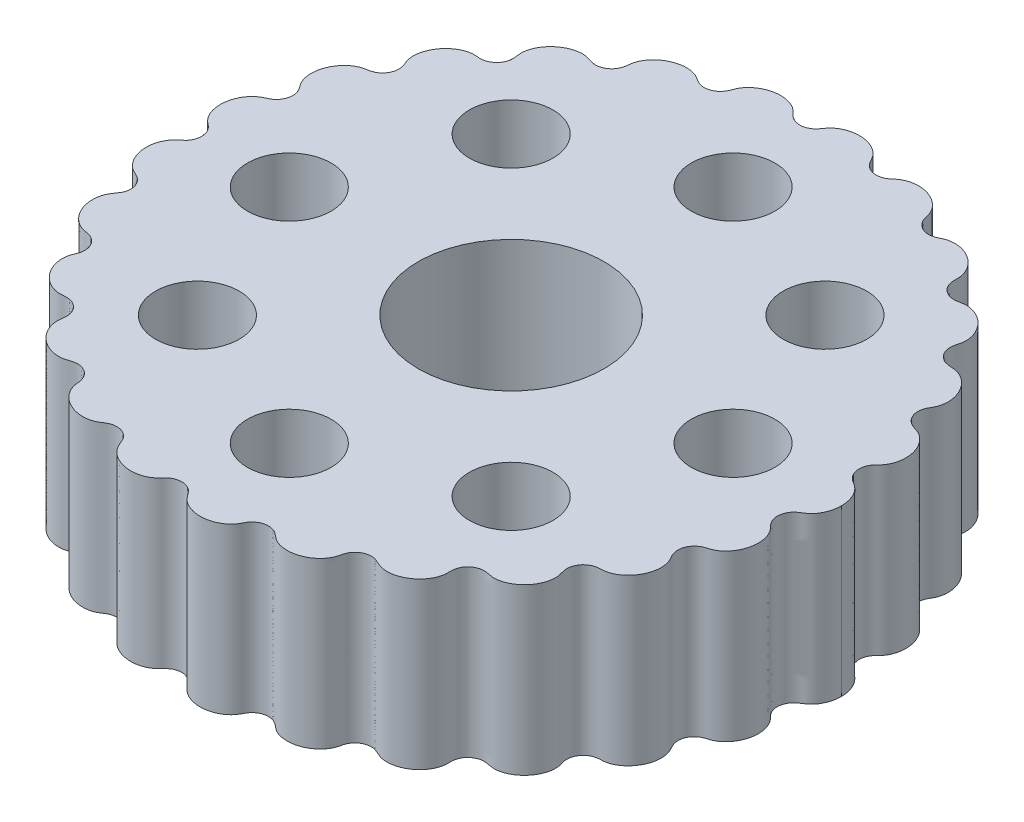
SolidWorks part; units mm, degrees
ref_plane "Front Plane" through (0, 0, 0) normal (0, 0, 1) x (1, 0, 0)
ref_plane "Top Plane" through (0, 0, 0) normal (0, 1, 0) x (1, 0, 0)
ref_plane "Right Plane" through (0, 0, 0) normal (1, 0, 0) x (0, 0, -1)
sketch "Sketch2" plane through (0, 0, 0) normal (0, 1, 0) x (1, 0, 0)
  line L0 (-31.5, 0) -> (33.5, 0) construction
  circle A0 centre (0, 0) radius 9
  circle A1 centre (0, 0) radius 21.5 construction
  circle A2 centre (0, 21.5) radius 4.05
  circle A3 centre (15.2028, 15.2028) radius 4.05
  circle A4 centre (21.5, 0) radius 4.05
  circle A5 centre (15.2028, -15.2028) radius 4.05
  circle A6 centre (0, -21.5) radius 4.05
  circle A7 centre (-15.2028, -15.2028) radius 4.05
  circle A8 centre (-21.5, 0) radius 4.05
  circle A9 centre (-15.2028, 15.2028) radius 4.05
  spline S0 degree 4 number of poles 351 (32.3077, -8.7825) -> (-30.5369, -7.93) construction
  spline S1 degree 4 number of poles 295 (33.5, 0) -> (-31.5, 0) construction
  spline S2 degree 4 number of poles 295 (33.5, 0) -> (-31.5, 0) construction
  spline S3 degree 1 poles (32, 0) (-30, 0) knots 0 0 1 1 construction
  spline S4 degree 1 poles (32, 0) (-30, 0) knots 0 0 1 1 construction
  spline S5 degree 3 number of poles 521 (32, 0) -> (-30, 0)
  spline S6 degree 3 number of poles 521 (-30, 0) -> (32, 0)
  point P29 (0, 0)
  point P36 (0, 0)
  dimension "D2" = 18
  dimension "D3" = 43
  dimension "D4" = 8.1
  dimension "D1" = 1.5
  dimension "D5" = 8
extrude "Boss-Extrude1" add sketch "Sketch2" along normal blind 16
